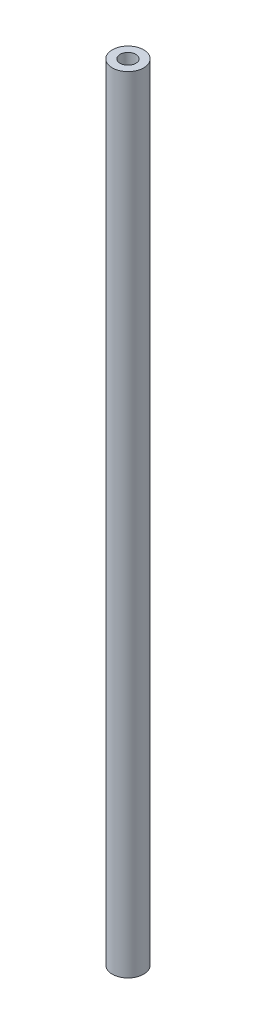
SolidWorks part; units mm, degrees
ref_plane "Alzado" through (0, 0, 0) normal (0, 0, 1) x (1, 0, 0)
ref_plane "Planta" through (0, 0, 0) normal (0, 1, 0) x (1, 0, 0)
ref_plane "Vista lateral" through (0, 0, 0) normal (1, 0, 0) x (0, 0, -1)
sketch "Croquis1" plane through (0, 0, 0) normal (0, 1, 0) x (1, 0, 0)
  circle A0 centre (0, 0) radius 4
  circle A1 centre (0, 0) radius 2
  dimension "D1" = 8
  dimension "D2" = 4
extrude "Saliente-Extruir1" add sketch "Croquis1" along normal blind 200
